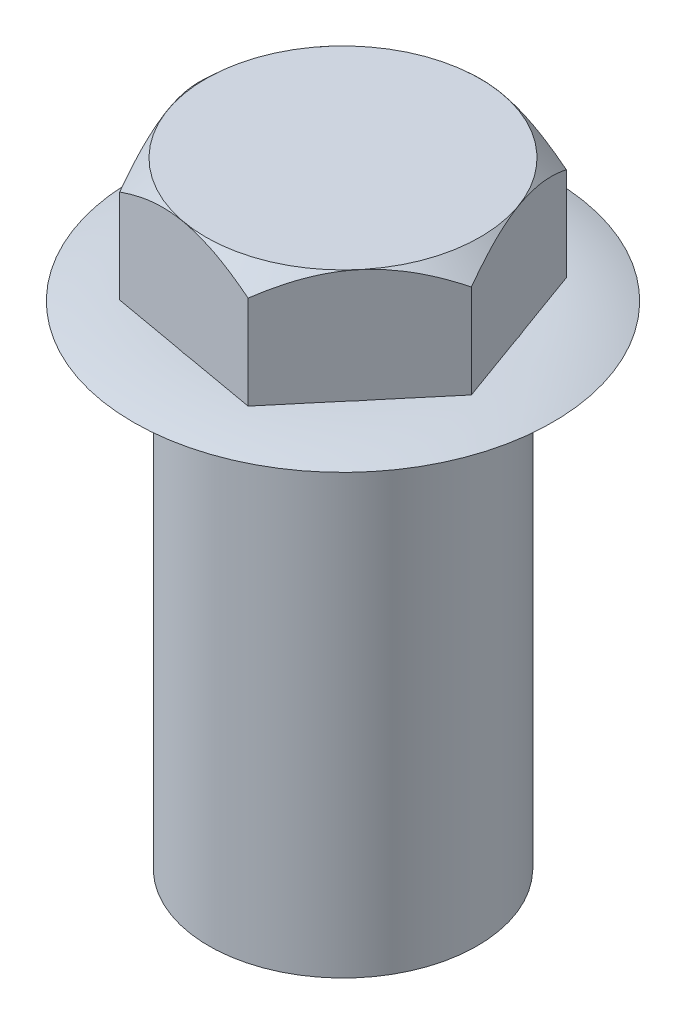
SolidWorks part; units mm, degrees
ref_plane "Front Plane" through (0, 0, 0) normal (0, 0, 1) x (1, 0, 0)
ref_plane "Top Plane" through (0, 0, 0) normal (0, 1, 0) x (1, 0, 0)
ref_plane "Right Plane" through (0, 0, 0) normal (1, 0, 0) x (0, 0, -1)
sketch "Sketch1" plane through (0, 0, 0) normal (0, 0, 1) x (1, 0, 0)
  line L0 (0, 0) -> (0, 18.0806) construction
  line L1 (0, 0) -> (1.775, 0)
  line L2 (1.775, 0) -> (1.775, 6.5)
  line L3 (1.775, 6.5) -> (2.775, 6.5)
  line L4 (0, 6.64) -> (1.8186, 6.64)
  line L5 (0, 0) -> (0, 6.64)
  arc A0 (2.775, 6.5) -> (1.8186, 6.64) centre (1.8732, 3.6772) ccw
  dimension "D1" = 3.55
  dimension "D2" = 6.5
  dimension "D3" = 1
revolve "Revolve1" add sketch "Sketch1" angle 360 about L0
sketch "Sketch2" plane through (0, 6.64, 0) normal (0, 1, 0) x (1, 0, 0)
  line L1 (1.3493, 1.6046) -> (-0.715, 1.9708)
  line L2 (-0.715, 1.9708) -> (-2.0643, 0.3662)
  line L3 (-2.0643, 0.3662) -> (-1.3493, -1.6046)
  line L4 (-1.3493, -1.6046) -> (0.715, -1.9708)
  line L5 (0.715, -1.9708) -> (2.0643, -0.3662)
  line L6 (2.0643, -0.3662) -> (1.3493, 1.6046)
  circle A0 centre (0, 0) radius 1.8156 construction
extrude "Boss-Extrude1" add sketch "Sketch2" along normal blind 1.5
sketch "Sketch3" plane through (0, 0, 0) normal (0, 0, 1) x (1, 0, 0)
  line L0 (0, 0) -> (0, 11.6808) construction
  line L1 (1.1116, 8.796) -> (2.4224, 7.5735)
  line L2 (2.4224, 7.5735) -> (2.4224, 8.796)
  line L3 (2.4224, 8.796) -> (1.1116, 8.796)
  point P6 (2.4224, 7.5735)
revolve "Cut-Revolve1" cut sketch "Sketch3" angle 360 about L0
